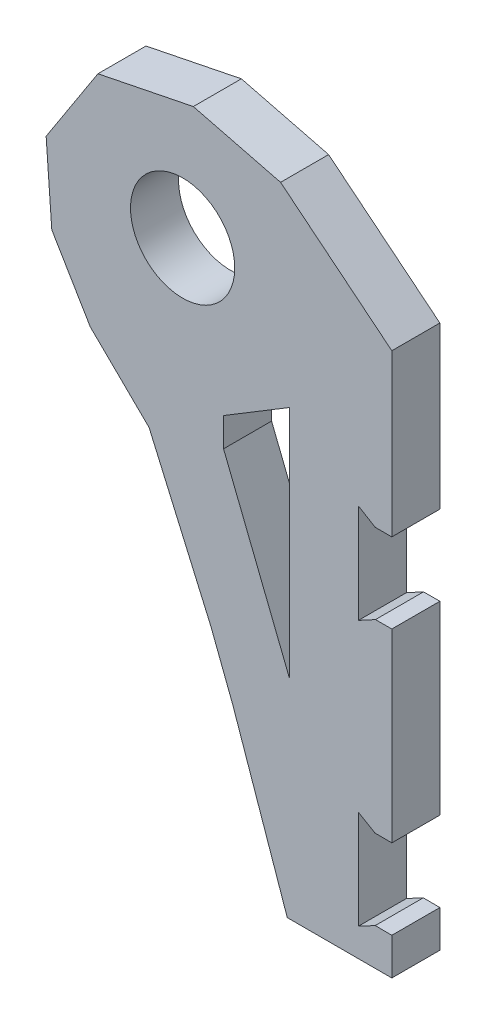
SolidWorks part; units mm, degrees
ref_plane "前视基准面" through (0, 0, 0) normal (0, 0, 1) x (1, 0, 0)
ref_plane "上视基准面" through (0, 0, 0) normal (0, 1, 0) x (1, 0, 0)
ref_plane "右视基准面" through (0, 0, 0) normal (1, 0, 0) x (0, 0, -1)
sketch "草图1" plane through (0, 0, 0) normal (0, 0, 1) x (1, 0, 0)
  line L0 (10.6557, -51.1335) -> (26.9757, -51.1326)
  line L1 (-20.0964, 13.3535) -> (-10.914, 4.3399)
  line L2 (0.7068, 7.2737) -> (0.7068, 11.7755)
  line L3 (11.0169, 18.0167) -> (11.0169, -18.6592)
  line L4 (21.7548, -5.3995) -> (21.7548, 10.0788)
  line L5 (26.9757, -32.8653) -> (26.9757, -3.9498)
  line L6 (26.9757, -51.1326) -> (26.9757, -45.356)
  line L7 (21.7548, -46.7446) -> (24.3816, -45.3386)
  line L8 (24.3816, -45.3386) -> (26.9757, -45.356)
  line L9 (26.9757, -3.9498) -> (24.4234, -3.9527)
  line L10 (24.4234, -3.9527) -> (21.7548, -5.3995)
  line L11 (26.9757, -32.8653) -> (24.3411, -32.8475)
  line L12 (24.3411, -32.8475) -> (21.7548, -31.3357)
  line L13 (21.7548, 10.0788) -> (24.3888, 8.4984)
  line L14 (24.3888, 8.4984) -> (26.9757, 8.501)
  line L17 (9.6078, 47.7536) -> (-4.0113, 51.1883)
  line L21 (26.9757, 14.3375) -> (26.9757, 33.6681)
  line L23 (26.9757, 33.6681) -> (9.6078, 47.7536)
  line L24 (-1.2759, -17.6979) -> (2.1409, -26.5918)
  line L26 (-4.0113, 51.1883) -> (-18.903, 48.1778)
  line L27 (0.7068, 11.7755) -> (11.0169, 18.0167)
  line L32 (11.0169, -18.6592) -> (0.7068, 7.2737)
  line L34 (-26.9901, 35.6877) -> (-26.1063, 23.478)
  line L37 (2.1409, -26.5918) -> (10.6557, -51.1335)
  line L39 (-18.903, 48.1778) -> (-26.9901, 35.6877)
  line L40 (-26.1063, 23.478) -> (-20.0964, 13.3535)
  line L42 (-10.914, 4.3399) -> (-1.2759, -17.6979)
  line L43 (21.7548, -46.7446) -> (21.7548, -31.3357)
  line L44 (26.9757, 8.501) -> (26.9757, 14.3375)
  circle A0 centre (-5.6841, 32.5811) radius 8.1374
extrude "凸台-拉伸1" add sketch "草图1" along normal blind 7.5 contours L23 L17 L26 L39 L34 L40 L1 L42 L24 L37 L0 L6 L8 L7 L43 L12 L11 L5 L9 L10 L4 L13 L14 L44 L21
